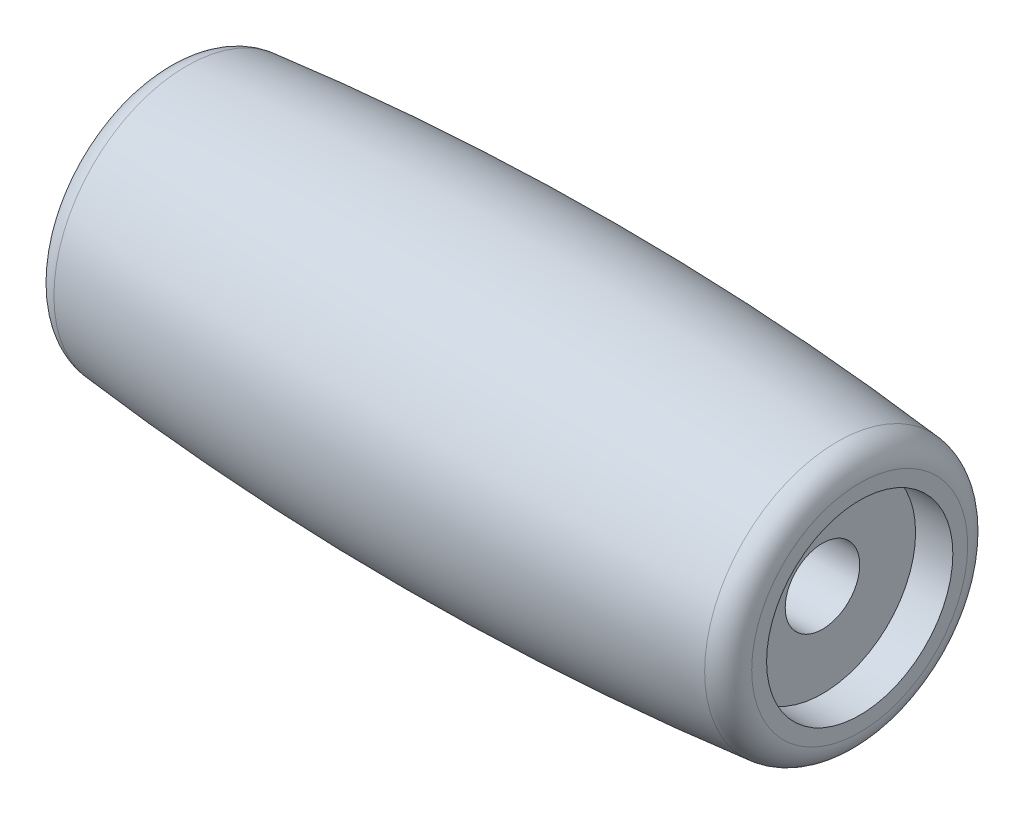
SolidWorks part; units mm, degrees
ref_plane "Front Plane" through (0, 0, 0) normal (0, 0, 1) x (1, 0, 0)
ref_plane "Top Plane" through (0, 0, 0) normal (0, 1, 0) x (1, 0, 0)
ref_plane "Right Plane" through (0, 0, 0) normal (1, 0, 0) x (0, 0, -1)
sketch "Sketch1" plane through (0, 0, 0) normal (0, 0, 1) x (1, 0, 0)
  line L0 (0, 0) -> (0, 6) construction
  line L1 (0, 0) -> (9.5934, 0) construction
  line L2 (-12.5, 1.5) -> (12.5, 1.5)
  line L3 (12.5, 1.5) -> (12.5, 3.75)
  line L4 (12.5, 3.75) -> (14, 3.75)
  line L5 (14, 3.75) -> (14, 4.3486)
  line L6 (-14, 3.75) -> (-14, 4.3486)
  line L7 (-12.5, 3.75) -> (-14, 3.75)
  line L8 (-12.5, 1.5) -> (-12.5, 3.75)
  arc A0 (-13.1, 5.3436) -> (13.1, 5.3436) centre (0, -125.0417) cw
  arc A1 (14, 4.3486) -> (13.1, 5.3436) centre (13, 4.3486) ccw
  arc A2 (-14, 4.3486) -> (-13.1, 5.3436) centre (-13, 4.3486) cw
  point P13 (0, 1.5)
  point P15 (0, 6)
  point P18 (14, 5.25)
  point P21 (-14, 5.25)
  dimension "D7" = 1
  dimension "D1" = 1.5
  dimension "D2" = 3.75
  dimension "D3" = 1.5
  dimension "D4" = 1.5
  dimension "D5" = 14
  dimension "D6" = 6
revolve "Revolve1" add sketch "Sketch1" angle 360 about L1
